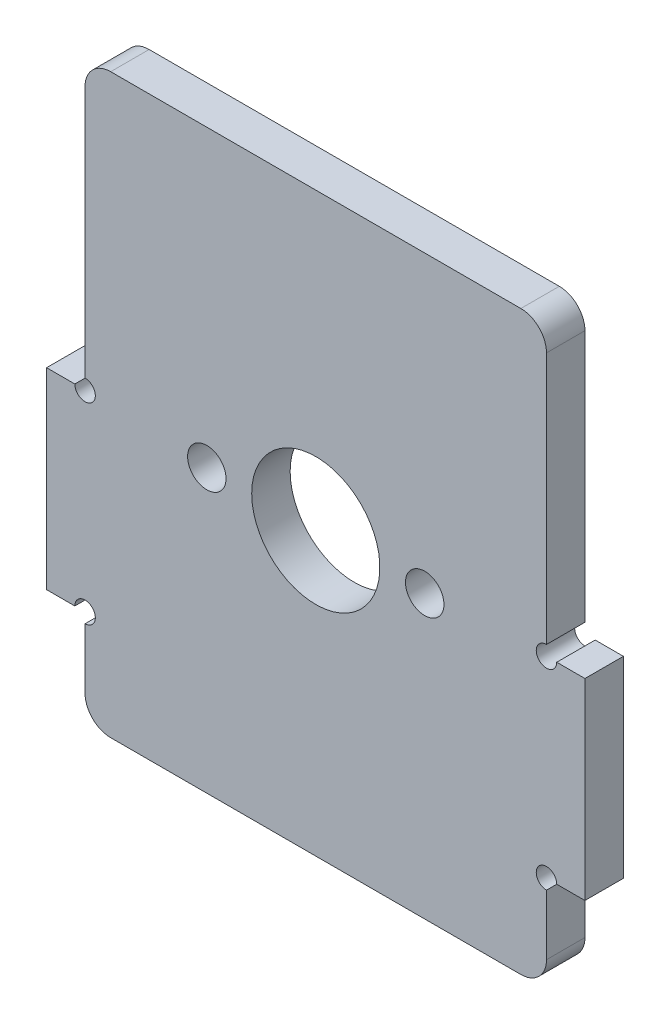
SolidWorks part; units mm, degrees
material "Thornel Mat VMA"
ref_plane "Front Plane" through (0, 0, 0) normal (0, 0, 1) x (1, 0, 0)
ref_plane "Top Plane" through (0, 0, 0) normal (0, 1, 0) x (1, 0, 0)
ref_plane "Right Plane" through (0, 0, 0) normal (1, 0, 0) x (0, 0, -1)
sketch "Sketch1" plane through (0, 0, 0) normal (0, 0, 1) x (1, 0, 0)
  line L0 (0, 0) -> (0, 15) construction
  line L1 (-18, -15) -> (18, -15)
  line L2 (-18, -15) -> (-18, 15)
  line L3 (-18, 15) -> (18, 15)
  line L4 (18, -15) -> (18, 15)
  line L5 (-18, -15) -> (18, 15) construction
  line L6 (-18, 15) -> (18, -15) construction
  line L7 (-21, -7.5) -> (-15, -7.5)
  line L8 (-21, -7.5) -> (-21, 7.5)
  line L9 (-21, 7.5) -> (-15, 7.5)
  line L10 (-15, -7.5) -> (-15, 7.5)
  line L11 (-21, -7.5) -> (-15, 7.5) construction
  line L12 (-21, 7.5) -> (-15, -7.5) construction
  line L13 (21, 7.5) -> (15, -7.5) construction
  line L14 (21, -7.5) -> (15, 7.5) construction
  line L15 (15, -7.5) -> (15, 7.5)
  line L16 (21, 7.5) -> (15, 7.5)
  line L17 (21, -7.5) -> (21, 7.5)
  line L18 (21, -7.5) -> (15, -7.5)
  point P0 (0, 0)
  point P6 (-18, 0)
  point P17 (18, 0)
  dimension "D1" = 36
  dimension "D2" = 30
  dimension "D3" = 6
  dimension "D4" = 15
extrude "Boss-Extrude1" add sketch "Sketch1" along normal blind 3 contours L4 L18 L15 L16 L3 L2 L9 L10 L7 L1 | L9 L8 L7 L2 | L7 L10 L9 L2 | L18 L17 L16 L4 | L18 L4 L16 L15
sketch "Sketch3" plane through (0, 0, 0) normal (0, 0, -1) x (-1, 0, 0)
  line L0 (18, 7.5) -> (18, 15) construction
  line L1 (-18, 15) -> (18, 15)
  line L2 (-18, 15) -> (-18, 30)
  line L3 (-18, 30) -> (18, 30)
  line L4 (18, 15) -> (18, 30)
  dimension "D1" = 15
extrude "Boss-Extrude2" add sketch "Sketch3" against normal up to surface (3 mm away) up to face at (0, 0, 3)
sketch "Sketch4" plane through (0, 0, 0) normal (0, 0, -1) x (-1, 0, 0)
  line L0 (0, 30) -> (0, 7) construction
  line L1 (18, 30) -> (-18, 30) construction
  line L2 (0, 7) -> (-8.5, 7) construction
  circle A0 centre (0, 7) radius 5
  circle A1 centre (-8.5, 7) radius 1.5
  circle A2 centre (8.5, 7) radius 1.5
  dimension "D2" = 10
  dimension "D3" = 3
  dimension "D4" = 17
  dimension "D1" = 23
extrude "Cut-Extrude1" cut sketch "Sketch4" against normal through all
sketch "Sketch5" plane through (0, 0, 0) normal (0, 0, -1) x (-1, 0, 0)
  circle A0 centre (-18, 7.5) radius 0.8
  circle A1 centre (-18, -7.5) radius 0.8
  circle A2 centre (18, 7.5) radius 0.8
  circle A3 centre (18, -7.5) radius 0.8
  dimension "D1" = 1.6
extrude "Cut-Extrude2" cut sketch "Sketch5" against normal through all
fillet "Fillet1" radius 2 4 edges at (18, -15, 1.5) (-18, -15, 1.5) (-18, 30, 1.5) (18, 30, 1.5)
